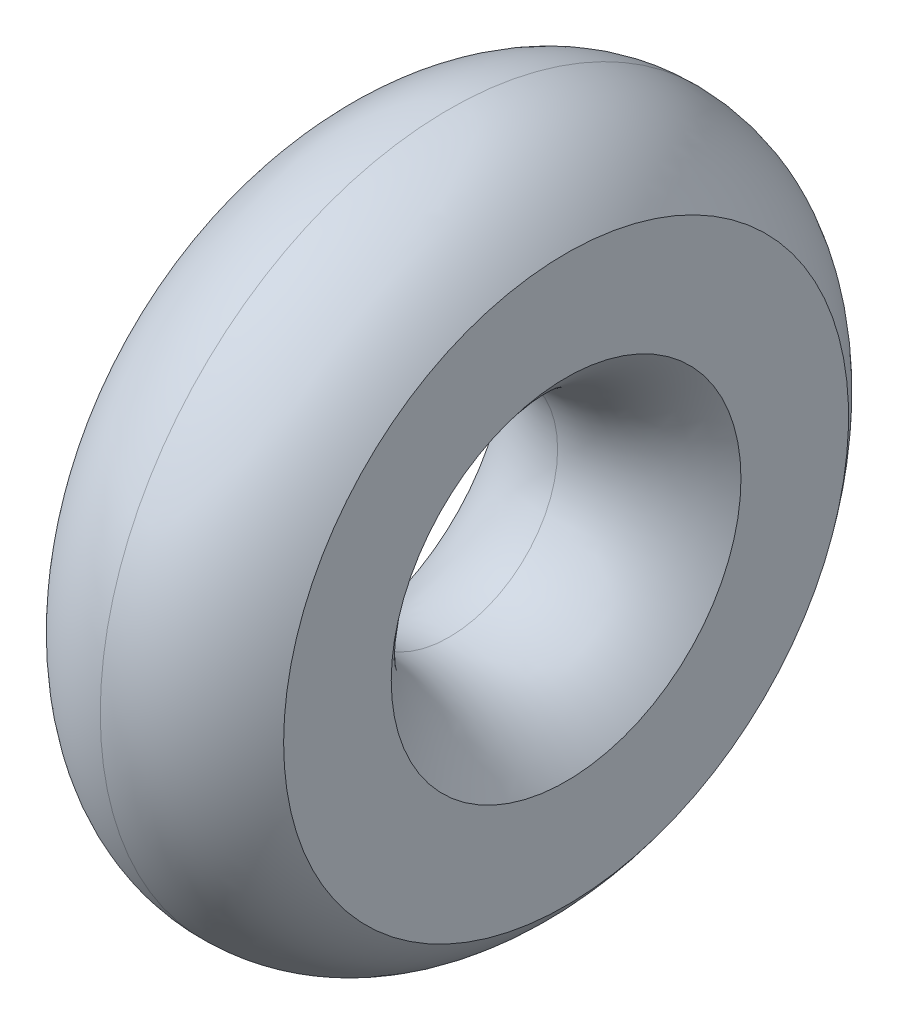
SolidWorks part; units mm, degrees
ref_plane "前视基准面" through (0, 0, 0) normal (0, 0, 1) x (1, 0, 0)
ref_plane "上视基准面" through (0, 0, 0) normal (0, 1, 0) x (1, 0, 0)
ref_plane "右视基准面" through (0, 0, 0) normal (1, 0, 0) x (0, 0, -1)
sketch "草图1" plane through (0, 0, 0) normal (0, 0, 1) x (1, 0, 0)
  line L0 (-55.976, 0) -> (61.6003, 0) construction
sketch "草图2" plane through (7.3024, -265.7307, 26.0034) normal (0, -0.0974, -0.9952) x (-1, 0, 0)
  line L0 (21.481, 396.6633) -> (18.4209, 396.6633) construction
  line L1 (-11.4036, 307.3367) -> (-13.2607, 307.3367) construction
  line L2 (-10.804, 267) -> (-10.804, 395.3932) construction
  line L3 (-10.804, 267) -> (-10.804, 395.3932) construction
  line L4 (32.6899, 372) -> (32.6899, 332)
  line L5 (-54.298, 372) -> (-54.298, 332)
  spline S0 degree 2 poles (-54.298, 332) (-35.804, 307.3367) (-10.804, 307.3367) knots 0 0 0 1 1 1
  spline S1 degree 2 poles (-54.298, 372) (-35.804, 396.6633) (-10.804, 396.6633) knots 0 0 0 1 1 1
  spline S2 degree 2 poles (32.6899, 332) (14.196, 307.3367) (-10.804, 307.3367) knots 0 0 0 1 1 1
  spline S3 degree 2 poles (32.6899, 372) (14.196, 396.6633) (-10.804, 396.6633) knots 0 0 0 1 1 1
  dimension "D1" = 50
  dimension "D2" = 50
revolve "旋转1" add sketch "草图2" angle 360 about L0
